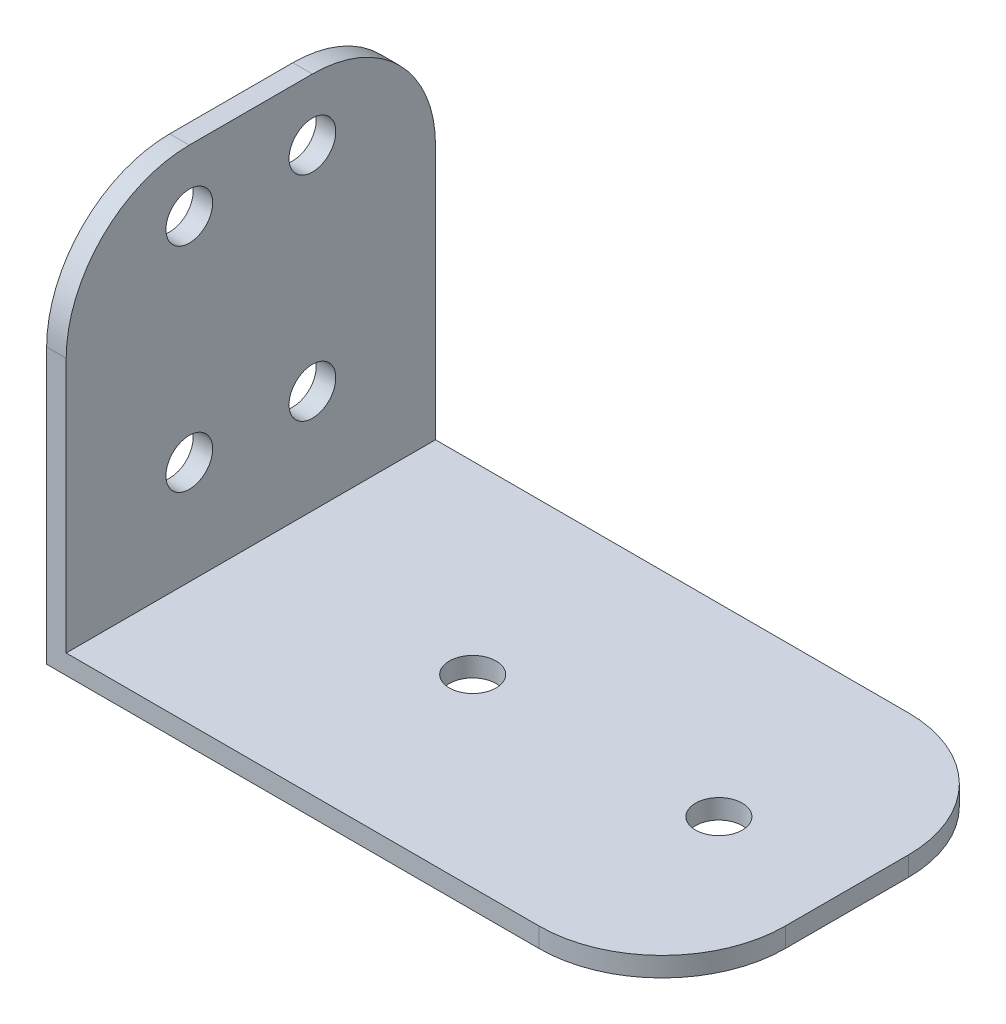
SolidWorks part; units mm, degrees
ref_plane "Front Plane" through (0, 0, 0) normal (0, 0, 1) x (1, 0, 0)
ref_plane "Top Plane" through (0, 0, 0) normal (0, 1, 0) x (1, 0, 0)
ref_plane "Right Plane" through (0, 0, 0) normal (1, 0, 0) x (0, 0, -1)
sketch "Sketch2" plane through (0, 0, 0) normal (0, 0, 1) x (1, 0, 0)
  line L0 (0, 0) -> (50, 0)
  line L1 (0, 0) -> (0, 32.32)
  line L2 (1.5875, 1.5875) -> (50, 1.5875)
  line L3 (1.5875, 1.5875) -> (1.5875, 32.32)
  line L4 (0, 32.32) -> (1.5875, 32.32)
  line L5 (50, 1.5875) -> (50, 0)
  dimension "D1" = 32.32
  dimension "D2" = 50
  dimension "D3" = 1.5875
extrude "Boss-Extrude1" add sketch "Sketch2" along normal mid plane 30
hole_wizard "#6 Clearance Hole1" positions "Sketch4" profile "Sketch3" hole size "#6" standard "ANSI Inch"
sketch "Sketch4" plane through (0, 0, 0) normal (-1, 0, 0) x (0, 0, 1)
  line L0 (0, 0) -> (0, 32.32) construction
  line L1 (15, 32.32) -> (-15, 32.32) construction
  line L3 (15, 0) -> (-15, 0) construction
  line L5 (-15, 32.32) -> (-15, 0) construction
  point P0 (-5, 27.32)
  point P2 (5, 10)
  point P19 (5, 27.32)
  point P21 (-5, 10)
  dimension "D1" = 5
  dimension "D2" = 10
  dimension "D3" = 10
  dimension "D4" = 10
sketch "Sketch3" plane through (0, 27.32, -5) normal (0, 1, 0) x (0, 0, 1)
  line L0 (0, 0) -> (0, 2.7273)
  line L1 (0, 2.7273) -> (1.8986, 1.5865)
  line L2 (1.8986, 1.5865) -> (1.8986, 0)
  line L5 (1.8986, 0) -> (0, 0)
  line L10 (0, 2.7273) -> (-1.8987, 1.5865) construction
  line L11 (0, -6.35) -> (0, 107.95) construction
  dimension "Hole Dia." = 3.7973
  dimension "Hole Depth" = 1.5865
  dimension "Drill Angle" = 118
fillet "Fillet1" radius 10 4 edges at (0.7937, 32.32, 15) (0.7937, 32.32, -15) (50, 0.7937, -15) (50, 0.7937, 15)
hole_wizard "#6 Clearance Hole2" positions "Sketch6" profile "Sketch5" hole size "#6" standard "ANSI Inch" end condition through all
sketch "Sketch6" plane through (0, 0, 0) normal (0, -1, 0) x (-1, 0, 0)
  line L0 (0, 0) -> (-50, 0) construction
  line L1 (-50, -5) -> (-50, 5) construction
  point P0 (-19.61, 0)
  point P2 (-39.61, 0)
  dimension "D1" = 20
  dimension "D2" = 19.61
sketch "Sketch5" plane through (19.61, 0, 0) normal (1, 0, 0) x (0, 0, -1)
  line L0 (0, 0) -> (0, 32.32)
  line L1 (0, 32.32) -> (1.8986, 32.32)
  line L2 (1.8986, 32.32) -> (1.8986, 0)
  line L5 (1.8986, 0) -> (0, 0)
  line L11 (0, -6.35) -> (0, 107.95) construction
  dimension "Thru Hole Dia." = 3.7973
  dimension "Thru Hole Depth" = 32.32
